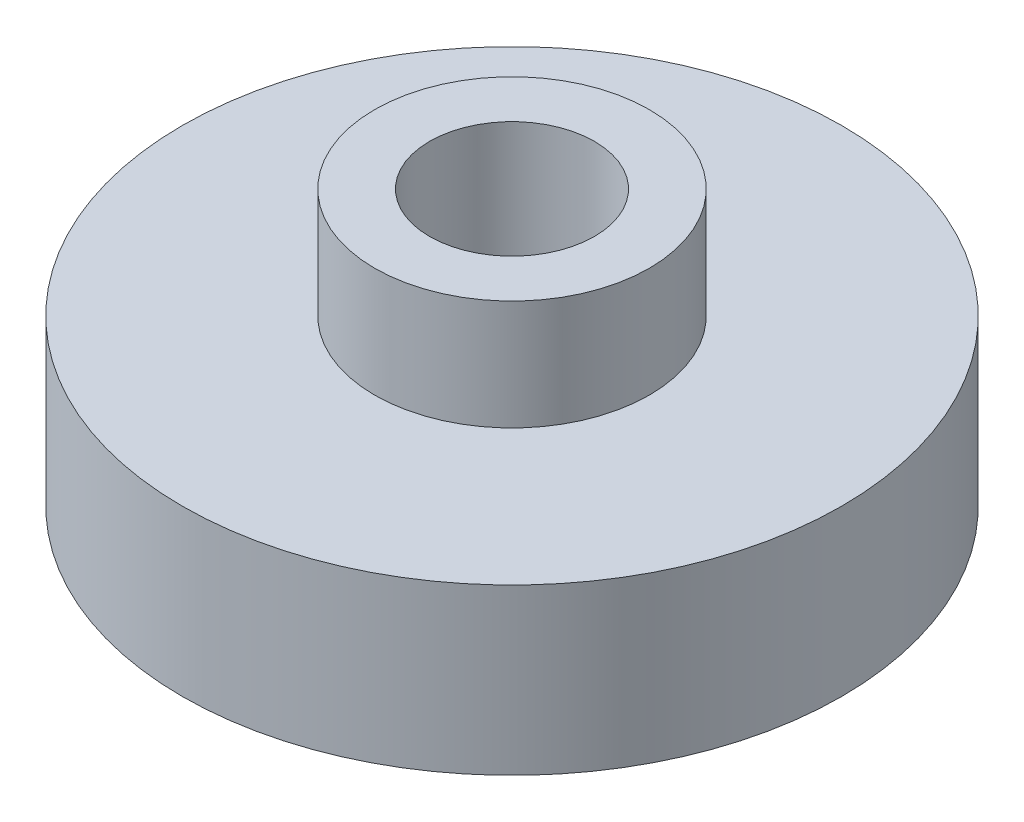
SolidWorks part; units mm, degrees
material "聚脂树脂"
ref_plane "前视基准面" through (0, 0, 0) normal (0, 0, 1) x (1, 0, 0)
ref_plane "上视基准面" through (0, 0, 0) normal (0, 1, 0) x (1, 0, 0)
ref_plane "右视基准面" through (0, 0, 0) normal (1, 0, 0) x (0, 0, -1)
other "Configuration Table"
sketch "草图1" plane through (0, 0, 0) normal (0, 1, 0) x (1, 0, 0)
  circle A0 centre (0, 0) radius 2.5
  circle A1 centre (0, 0) radius 1.5
  dimension "D1" = 3
  dimension "D2" = 5
extrude "凸台-拉伸1" add sketch "草图1" along normal blind 2
sketch "草图2" plane through (0, 0, 0) normal (0, -1, 0) x (1, 0, 0)
  circle A0 centre (0, 0) radius 1.5
  circle A1 centre (0, 0) radius 6
  dimension "D1" = 3
  dimension "D2" = 12
extrude "凸台-拉伸2" add sketch "草图2" along normal blind 3
